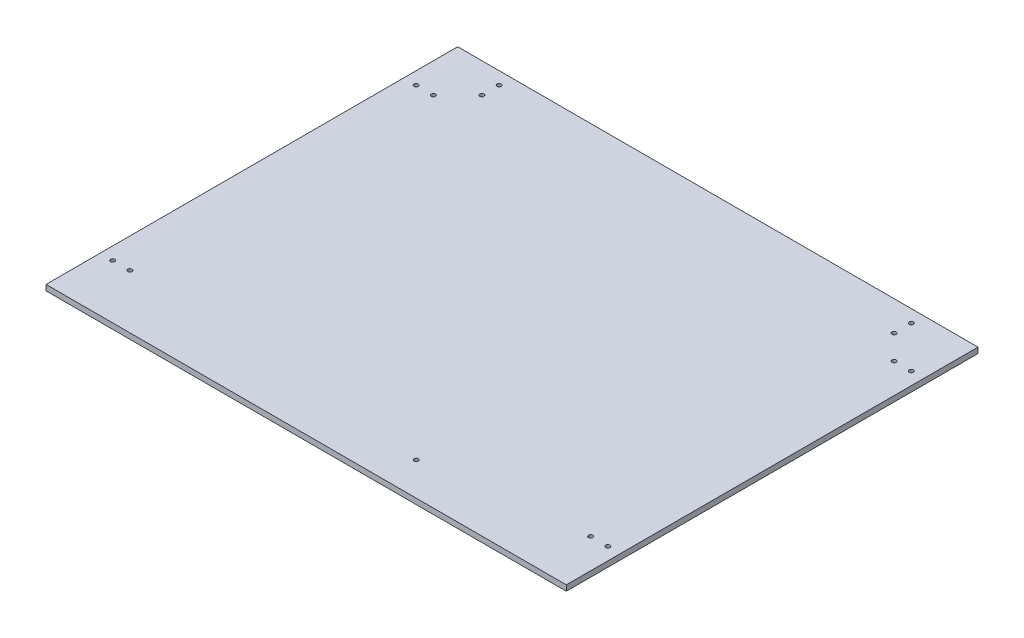
SolidWorks part; units mm, degrees
material "Pino"
ref_plane "Piano frontale" through (0, 0, 0) normal (0, 0, 1) x (1, 0, 0)
ref_plane "Piano superiore" through (0, 0, 0) normal (0, 1, 0) x (1, 0, 0)
ref_plane "Piano destro" through (0, 0, 0) normal (1, 0, 0) x (0, 0, -1)
sketch "Schizzo1" plane through (0, 0, 0) normal (0, 1, 0) x (1, 0, 0)
  line L1 (-279, 220.75) -> (279, 220.75)
  line L2 (-279, 220.75) -> (-279, -220.75)
  line L3 (-279, -220.75) -> (279, -220.75)
  line L4 (279, 220.75) -> (279, -220.75)
  line L5 (-279, 220.75) -> (279, -220.75) construction
  line L6 (-279, -220.75) -> (279, 220.75) construction
  point P4 (0, 0)
  dimension "D1" = 558
  dimension "D2" = 441.5
extrude "Estrusione-Estrusione1" add sketch "Schizzo1" along normal blind 6
sketch "Schizzo2" plane through (0, 0, 0) normal (0, -1, 0) x (-1, 0, 0)
  circle A0 centre (-221, 207.25) radius 2.25
  circle A1 centre (-221, 188.75) radius 2.25
  circle A2 centre (-247, 162.75) radius 2.25
  circle A3 centre (-265.5, 162.75) radius 2.25
  circle A4 centre (221, 207.25) radius 2.25
  circle A5 centre (221, 188.75) radius 2.25
  circle A6 centre (247, 162.75) radius 2.25
  circle A7 centre (265.5, 162.75) radius 2.25
  circle A8 centre (265.5, -162.75) radius 2.25
  circle A9 centre (247, -162.75) radius 2.25
  circle A10 centre (-265.5, -162.75) radius 2.25
  circle A11 centre (-247, -162.75) radius 2.25
  circle A12 centre (-82.5, -185.25) radius 2.25
  dimension "D1" = 4.5
extrude "Taglio-Estrusione1" cut sketch "Schizzo2" against normal blind 10
